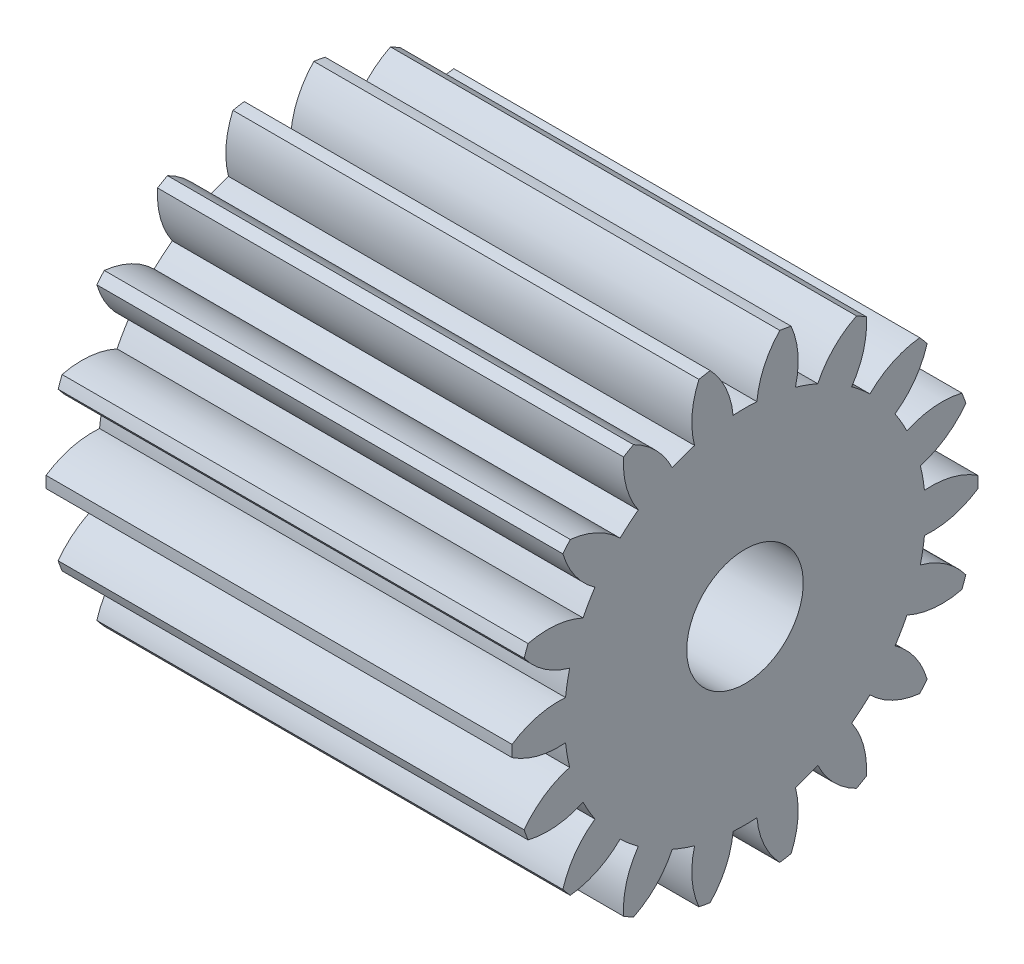
SolidWorks part; units mm, degrees
ref_plane "Plane1" through (0, 0, 0) normal (0, 0, 1) x (1, 0, 0)
ref_plane "Plane2" through (0, 0, 0) normal (0, 1, 0) x (1, 0, 0)
ref_plane "Plane3" through (0, 0, 0) normal (1, 0, 0) x (0, 0, -1)
sketch "HoldingSke" plane through (0, 0, 0) normal (0, 1, 0) x (1, 0, 0)
  line L0 (0, 0) -> (1.9021, -0.618)
  line L1 (-15, 0) -> (100, 0) construction
  line L2 (0, 0) -> (-2.1039, 2.3779)
  line L3 (0, 0) -> (-11.863, 4.5341)
  line L4 (0, 0) -> (8.2133, 2.6687)
  line L5 (0, 0) -> (-46.8476, -17.4728)
  line L6 (0, 0) -> (-8.2896, -5.593)
  line L7 (-2.1039, 2.3779) -> (8.6586, 51.2059)
  line L8 (-76.2, 54.61) -> (-76.1, 54.61)
  line L9 (-71.009, 38.7566) -> (-53.1078, 45.2721)
  line L10 (-76.2, 71.12) -> (104.1128, 71.12)
  line L11 (0, 0) -> (-10, 0)
  line L12 (-76.2, 101.6) -> (-76.181, 101.6)
  line L13 (24.9733, 27.94) -> (52.9518, 28.4284)
  line L14 (24.9733, 27.94) -> (24.9743, 27.94)
  line L15 (24.9733, 27.94) -> (100.4006, 29.5858)
  line L16 (-63.627, -0.5) -> (-12.827, -0.5)
  circle A0 centre (0, 0) radius 0.4
  circle A1 centre (0, 0) radius 3.874
  circle A2 centre (0, 0) radius 37.5
  circle A3 centre (0, 0) radius 1.25
  dimension "MHD" = 7.748
  dimension "Hub_dia" = 75
  dimension "Bore" = 0.8
  dimension "MBD" = 2.5
  dimension "Num_teeth" = 18
  dimension "Pitch" = 2
  dimension "Overall_len" = 50
  dimension "Show_teeth" = 18
  dimension "Thickness" = 10
  dimension "OAL" = 50.0001
  dimension "T_dim" = 0.1
  dimension "Ap" = 20
  dimension "H" = 19.05
  dimension "Pitch_radius" = 180.3128
  dimension "Width" = 10
  dimension "Backlash" = 0.019
  dimension "Addendum_fac" = 1
  dimension "Dedendum_fac" = 1.25
  dimension "Clearance_fac" = 0.25
  dimension "Dedendum_add" = 0.001
  dimension "Module" = 0.5
sketch "BasProSke" plane through (0, 0, 0) normal (0, 1, 0) x (1, 0, 0)
  line L0 (-10, 0) -> (60, 0) construction
  line L1 (0, 0) -> (0, 5)
  line L2 (0, 0) -> (10, 0)
  line L3 (10, 0) -> (10, 5)
  line L4 (10, 5) -> (0, 5)
  dimension "Thickness" = 10
  dimension "Diameter" = 10
revolve "Base-Revolve" add sketch "BasProSke" angle 360 about L0
sketch "TooCutSke" plane through (0, 0, 0) normal (1, 0, 0) x (0, 0, -1)
  line L1 (0, 0) -> (0, 107) construction
  line L2 (0, 0) -> (-0.4254, 4.4798) construction
  line L3 (0, 0) -> (-1.5579, 8.835) construction
  line L4 (-0.4254, 4.4798) -> (-0.7789, 4.4175) construction
  arc A0 (0.2553, 3.8656) -> (-0.2553, 3.8656) centre (0, 0) ccw
  arc A1 (0.7686, 4.9663) -> (-0.7686, 4.9663) centre (0, 0) ccw
  circle A2 centre (0, 0) radius 4.5 construction
  circle A3 centre (0, 0) radius 4.2286 construction
  arc A4 (-0.2553, 3.8656) -> (-0.7686, 4.9663) centre (-2.0476, 3.6998) ccw
  arc A5 (0.7686, 4.9663) -> (0.2553, 3.8656) centre (2.0476, 3.6998) ccw
  dimension "Root_dia" = 7.748
  dimension "Overcut_dia" = 10.0508
  dimension "Pitch_dia" = 9
  dimension "Base_dia" = 8.4572
  dimension "Flank_rad" = 1.8
  dimension "Half_ang" = 10
  dimension "Half_CT" = 0.359
extrude "ToothCut" cut sketch "TooCutSke" along normal through all
fillet "Breaks" [suppressed] radius 0.01
fillet "RootFillets" [suppressed] radius 0.126
pattern_circular "TeethCuts" count 18 every 20 about axis through (-10, 0, 0) along (1, 0, 0) of "ToothCut", "RootFillets", "Breaks"
sketch "HubNeaOneSke" plane through (0, 0, 0) normal (-1, 0, 0) x (0, 0, 1)
  circle A0 centre (0, 0) radius 3.874
  dimension "Diameter" = 7.748
extrude "HubNearOne" [suppressed] add sketch "HubNeaOneSke" along normal blind 40.0001
sketch "HubNeaBotSke" plane through (0, 0, 0) normal (-1, 0, 0) x (0, 0, 1)
  circle A0 centre (0, 0) radius 3.874
  dimension "Diameter" = 7.748
extrude "HubNearBoth" [suppressed] add sketch "HubNeaBotSke" along normal blind 20
ref_plane "FarPln" through (10, 0, 0) normal (1, 0, 0) x (0, 0, -1)
sketch "HubFarSke" plane through (10, 0, 0) normal (1, 0, 0) x (0, 0, -1)
  circle A0 centre (0, 0) radius 3.874
  dimension "Diameter" = 7.748
extrude "HubFar" [suppressed] add sketch "HubFarSke" along normal blind 20
sketch "BorSke" plane through (0, 0, 0) normal (1, 0, 0) x (0, 0, -1)
  circle A0 centre (0, 0) radius 1.25
  dimension "Diameter" = 2.5
extrude "Bore" cut sketch "BorSke" along normal mid plane 100.0001
sketch "KeySke" plane through (0, 0, 0) normal (1, 0, 0) x (0, 0, -1)
  line L0 (-0.05, 0) -> (-0.05, 1.35)
  line L1 (-0.05, 1.35) -> (0.05, 1.35)
  line L2 (0.05, 1.35) -> (0.05, 0)
  line L3 (0, 0) -> (0, 34) construction
  line L4 (-0.05, 0) -> (0.05, 0)
  dimension "Offset" = 1.35
  dimension "Width" = 0.1
extrude "Keyway" [suppressed] cut sketch "KeySke" along normal mid plane 100.0001
pattern_circular "Keyway2" [suppressed] count 2 every 90 about axis through (-10, 0, 0) along (1, 0, 0)
equation "' \"Module@HoldingSke\" = 6.35"
equation "' \"Num_teeth@HoldingSke\" = 12"
equation "' \"Ap@HoldingSke\" =  20"
equation "' \"Ap@HoldingSke\" = 20"
equation "' \"Width@HoldingSke\" = 0.5 * 25.4"
equation "' \"Hub_dia@HoldingSke\"= 1 * 25.4"
equation "' \"Hub_dia@HoldingSke\" = 1 * 25.4"
equation "' \"Overall_len@HoldingSke\" = 1.0 * 25.4"
equation "' \"Bore@HoldingSke\" = 0.75 * 25.4"
equation "' \"T_dim@HoldingSke\" = 0.1 * 25.4"
equation "' \"Width@KeySke\" = 0.25 * 25.4"
equation "' \"Show_teeth@HoldingSke\" = 13"
equation "' \"Backlash@HoldingSke\" = 0.009 * 25.4"
equation "' \"Addendum_fac@HoldingSke\" = 1.0"
equation "' \"Dedendum_fac@HoldingSke\" = 1.25"
equation "' \"Dedendum_add@HoldingSke\" = 0.00005 * 25.4"
equation "' \"Clearance_fac@HoldingSke\" = 0.25"
equation "\"Pitch@HoldingSke\" = 1 / \"Module@HoldingSke\""
equation "\"Overcut_dia@TooCutSke\" = (\"Num_teeth@HoldingSke\" + 2 * \"Addendum_fac@HoldingSke\") / \"Pitch@HoldingSke\" + 0.002 * 25.4"
equation "\"Pitch_dia@TooCutSke\" = \"Num_teeth@HoldingSke\" / \"Pitch@HoldingSke\""
equation "\"Base_dia@TooCutSke\" = \"Num_teeth@HoldingSke\" / \"Pitch@HoldingSke\" * cos((\"Ap@HoldingSke\"  * 3.14159265 / 180))"
equation "\"Root_dia@TooCutSke\" = (\"Num_teeth@HoldingSke\" + 2) / \"Pitch@HoldingSke\" - 2 * (\"Addendum_fac@HoldingSke\" + \"Dedendum_fac@HoldingSke\") / \"Pitch@HoldingSke\" - \"Dedendum_add@HoldingSke\" * 2"
equation "\"Half_ang@TooCutSke\" = 180 / \"Num_teeth@HoldingSke\""
equation "\"Half_CT@TooCutSke\" = \"Num_teeth@HoldingSke\" / \"Pitch@HoldingSke\" * sin((3.14159265 / 2 / \"Num_teeth@HoldingSke\")) / 2 - 7 * \"Backlash@HoldingSke\" / 4"
equation "\"Flank_rad@TooCutSke\" = \"Num_teeth@HoldingSke\" / \"Pitch@HoldingSke\" / 5"
equation "\"Radius@RootFillets\" = \"Clearance_fac@HoldingSke\" / \"Pitch@HoldingSke\" + \"Dedendum_add@HoldingSke\""
equation "\"Break_rad@Breaks\" = 0.02 / \"Pitch@HoldingSke\""
equation "\"Thickness@HoldingSke\" = \"Width@HoldingSke\""
equation "\"OAL@HoldingSke\" = \"Thickness@HoldingSke\""
equation "\"MHD@HoldingSke\" = (\"Num_teeth@HoldingSke\" + 2) / \"Pitch@HoldingSke\" - 2 * (\"Addendum_fac@HoldingSke\" + \"Dedendum_fac@HoldingSke\")  / \"Pitch@HoldingSke\" - \"Dedendum_add@HoldingSke\" * 2"
equation "\"MHD@HoldingSke\" = ((sgn( \"MHD@HoldingSke\" - \"Hub_dia@HoldingSke\" )-1)*( \"MHD@HoldingSke\" - \"Hub_dia@HoldingSke\" ))/-2+ \"Hub_dia@HoldingSke\""
equation "\"OAL@HoldingSke\" = ((sgn( \"OAL@HoldingSke\" - \"Overall_len@HoldingSke\" )+1)*( \"OAL@HoldingSke\" - \"Overall_len@HoldingSke\" ))/2 + \"Overall_len@HoldingSke\" + 0.000002 * 25.4"
equation "\"Num_teeth@TeethCuts\" = int( \"Show_teeth@HoldingSke\" ) + 1"
equation "\"Num_teeth@TeethCuts\" = ((sgn( \"Num_teeth@TeethCuts\" - \"Num_teeth@HoldingSke\" )-1)*( \"Num_teeth@TeethCuts\" - \"Num_teeth@HoldingSke\" ))/-2+ \"Num_teeth@HoldingSke\""
equation "\"Num_teeth@TeethCuts\" = ((sgn( \"Num_teeth@TeethCuts\" - 2.0)+1)*( \"Num_teeth@TeethCuts\" - 2.0))/2 +2.0"
equation "\"Angle@TeethCuts\" = 360.0 / \"Num_teeth@HoldingSke\""
equation "\"Diameter@BasProSke\" = (\"Num_teeth@HoldingSke\" + 2 * \"Addendum_fac@HoldingSke\") / \"Pitch@HoldingSke\""
equation "\"Thickness@BasProSke\"  = \"Thickness@HoldingSke\""
equation "' \"Fillet_rad@BasProSke\" =  \"Thickness@HoldingSke\" * 0.05"
equation "' \"Fillet_rad@BasProSke\" = \"Thickness@HoldingSke\" * 0.05"
equation "\"MHD@HoldingSke\" = ((sgn( \"MHD@HoldingSke\" - \"Root_dia@TooCutSke\" )-1)*( \"MHD@HoldingSke\" - \"Root_dia@TooCutSke\" ))/-2+ \"Root_dia@TooCutSke\""
equation "\"Diameter@HubNeaOneSke\" = \"MHD@HoldingSke\""
equation "\"Length@HubNearOne\" = \"OAL@HoldingSke\" - \"Thickness@BasProSke\""
equation "\"Diameter@HubNeaBotSke\" = \"MHD@HoldingSke\""
equation "\"Length@HubNearBoth\" = ( \"OAL@HoldingSke\" - \"Thickness@BasProSke\" ) / 2.0"
equation "\"Thickness@FarPln\" = \"Thickness@BasProSke\""
equation "\"Diameter@HubFarSke\" = \"MHD@HoldingSke\""
equation "\"Length@HubFar\" = ( \"OAL@HoldingSke\" - \"Thickness@BasProSke\" ) / 2.0"
equation "\"Diameter@BorSke\" = \"MBD@HoldingSke\""
equation "\"D1@Bore\" = \"OAL@HoldingSke\" * 2.0"
equation "\"D1@Keyway\" = \"OAL@HoldingSke\" * 2.0"
equation "\"Offset@KeySke\" = \"T_dim@HoldingSke\" + \"MBD@HoldingSke\" / 2.0"
